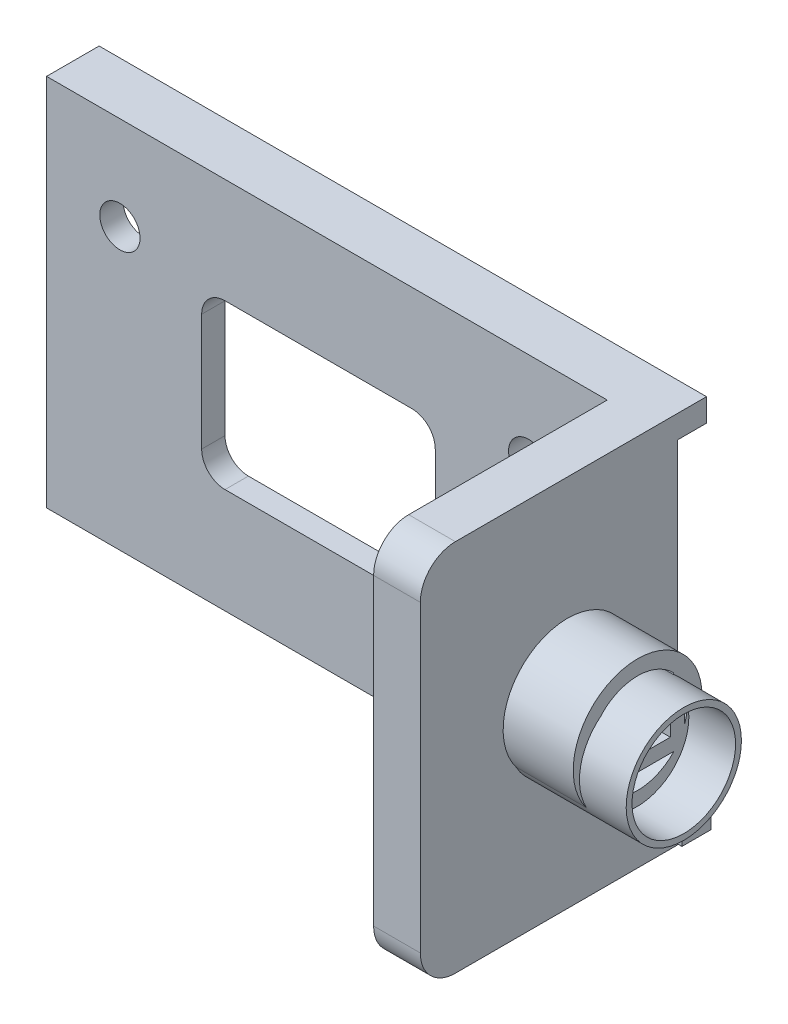
SolidWorks part; units mm, degrees
ref_plane "Front Plane" through (0, 0, 0) normal (0, 0, 1) x (1, 0, 0)
ref_plane "Top Plane" through (0, 0, 0) normal (0, 1, 0) x (1, 0, 0)
ref_plane "Right Plane" through (0, 0, 0) normal (1, 0, 0) x (0, 0, -1)
sketch "Sketch1" plane through (0, 0, 0) normal (0, 0, 1) x (1, 0, 0)
  line L1 (0, 0) -> (52, 0)
  line L2 (0, 0) -> (0, -32)
  line L3 (0, -32) -> (52, -32)
  line L4 (52, 0) -> (52, -32)
  dimension "D1" = 52
  dimension "D2" = 32
extrude "Boss-Extrude1" add sketch "Sketch1" along normal blind 2
ref_plane "Plane1" through (0, 0, 2) normal (0, 0, -1) x (-1, 0, 0)
sketch "Sketch2" plane through (0, 0, 2) normal (0, 0, -1) x (-1, 0, 0)
  line L1 (-48, 0) -> (-52, 0)
  line L2 (-48, 0) -> (-48, -32)
  line L3 (-48, -32) -> (-52, -32)
  line L4 (-52, 0) -> (-52, -32)
  dimension "D1" = 4
extrude "Boss-Extrude2" add sketch "Sketch2" against normal blind 20
fillet "Fillet1" radius 3 2 edges at (50, -32, 22) (50, 0, 22)
sketch "Sketch4" plane through (0, 0, 2) normal (0, 0, 1) x (1, 0, 0)
  line L0 (48, 0) -> (0, 0) construction
  circle A0 centre (41.2777, -8) radius 1.725
  circle A1 centre (6.2777, -8) radius 1.725
  dimension "D1" = 35
  dimension "D2" = 8
  dimension "D3" = 8
extrude "Cut-Extrude2" cut sketch "Sketch4" against normal up to surface (2 mm away) up to face at (26, -16, 0)
sketch "Sketch5" plane through (0, 0, 0) normal (0, 0, -1) x (-1, 0, 0)
  line L6 (0, 0) -> (0, -32) construction
  line L7 (-52.3955, -31.9041) -> (0, -31.9041)
  line L8 (-52.3955, -31.9041) -> (-52.3955, -29.9041)
  line L9 (-52.3955, -29.9041) -> (0, -29.9041)
  line L10 (0, -31.9041) -> (0, -29.9041)
  line L12 (-52, -1.966) -> (0, -2.1935)
  line L13 (0, 0) -> (0, -2.1935)
  line L14 (-52, 0) -> (0, 0)
  line L15 (-52, 0) -> (-52, -1.966)
  dimension "D1" = 2
extrude "Boss-Extrude3" add sketch "Sketch5" along normal blind 2.5
sketch "Sketch6" plane through (0, 0, 2) normal (0, 0, 1) x (1, 0, 0)
  line L0 (48, 0) -> (0, 0) construction
  line L1 (33.2777, -9) -> (13.2777, -9)
  line L2 (33.2777, -9) -> (33.2777, -23)
  line L3 (33.2777, -23) -> (13.2777, -23)
  line L4 (13.2777, -9) -> (13.2777, -23)
  circle A0 centre (6.2777, -8) radius 1.725 construction
  dimension "D3" = 7
  dimension "D1" = 14
  dimension "D2" = 20
  dimension "D4" = 9
extrude "Cut-Extrude3" cut sketch "Sketch6" against normal up to surface (2 mm away) up to face at (26, -31.9521, 0)
sketch "Sketch7" plane through (52, 0, 0) normal (1, 0, 0) x (0, 0, -1)
  line L0 (-22, -16) -> (2.0181, -16) construction
  line L1 (-12.4, -17.7) -> (-6.6, -17.7)
  line L2 (-12.4, -17.7) -> (-12.4, -14.3)
  line L3 (-12.4, -14.3) -> (-6.6, -14.3)
  line L4 (-6.6, -17.7) -> (-6.6, -14.3)
  line L5 (-22, -3) -> (-22, -29) construction
  line L6 (-9.5, -32) -> (-9.5, 5.4647) construction
  line L7 (-19, -32) -> (0, -32) construction
  line L8 (-13.6, -13.1) -> (-5.4, -13.1)
  line L9 (-5.4, -18.9) -> (-5.4, -13.1)
  line L10 (-13.6, -18.9) -> (-5.4, -18.9)
  line L11 (-13.6, -18.9) -> (-13.6, -13.1)
  dimension "D5" = 1.2
  dimension "D1" = 5.8
  dimension "D2" = 3.4
  dimension "D3" = 1.7
  dimension "D4" = 2.9
sketch "Sketch8" plane through (52, 0, 0) normal (1, 0, 0) x (0, 0, -1)
  line L0 (-9.3955, -16) -> (-9.3955, 10.2333) construction
  line L1 (-22, -16) -> (3.209, -16) construction
  line L2 (-22, -3) -> (-22, -29) construction
  circle A0 centre (-9.3955, -16) radius 4.25
  circle A1 centre (-9.3955, -16) radius 5.5166
extrude "Boss-Extrude4" add sketch "Sketch7" along normal blind 6
sketch "Sketch10" plane through (52, 0, 0) normal (1, 0, 0) x (0, 0, -1)
  circle A0 centre (-9.443, -16.9947) radius 4.4327
  circle A1 centre (-9.443, -16.9947) radius 4.9332
extrude "Boss-Extrude6" add sketch "Sketch10" along normal blind 10
extrude "Boss-Extrude5" add sketch "Sketch8" along normal blind 6
fillet "Fillet2" radius 2 4 edges at (13.2777, -9, 1) (13.2777, -23, 1) (33.2777, -9, 1) (33.2777, -23, 1)
